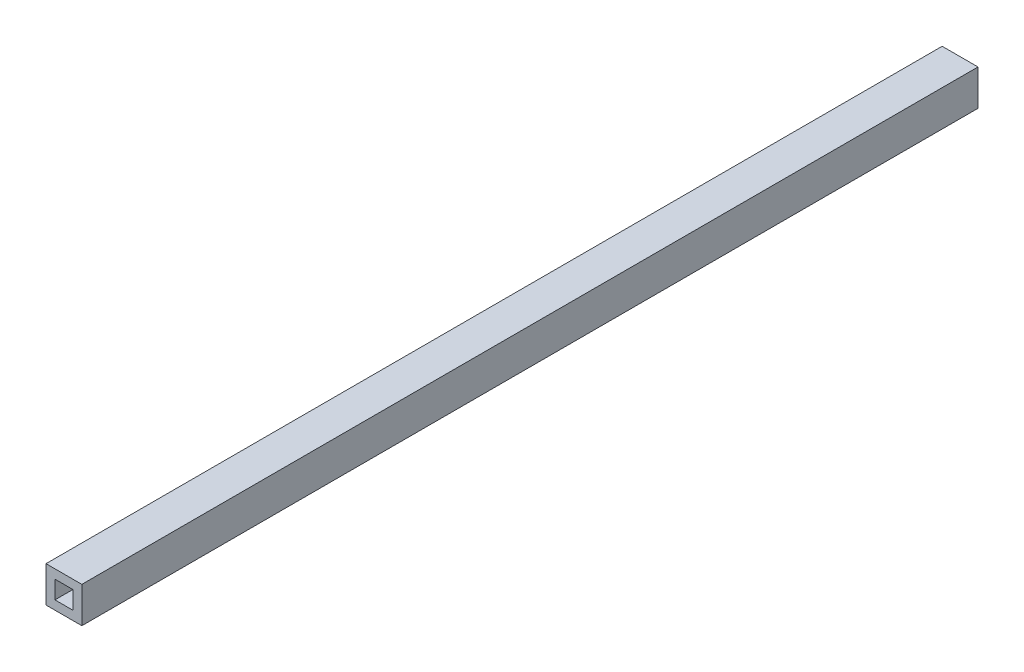
SolidWorks part; units mm, degrees
material "6063-O"
ref_plane "Front Plane" through (0, 0, 0) normal (0, 0, 1) x (1, 0, 0)
ref_plane "Top Plane" through (0, 0, 0) normal (0, 1, 0) x (1, 0, 0)
ref_plane "Right Plane" through (0, 0, 0) normal (1, 0, 0) x (0, 0, -1)
sketch "Sketch1" plane through (0, 0, 0) normal (0, 0, 1) x (1, 0, 0)
  line L1 (-10, -10) -> (10, -10)
  line L2 (-10, -10) -> (-10, 10)
  line L3 (-10, 10) -> (10, 10)
  line L4 (10, -10) -> (10, 10)
  line L5 (-10, -10) -> (10, 10) construction
  line L6 (-10, 10) -> (10, -10) construction
  point P0 (0, 0)
  dimension "D1" = 20
extrude "Extrude-Thin1" add sketch "Sketch1" along normal blind 500 thin thin type one direction reverse wall 5
